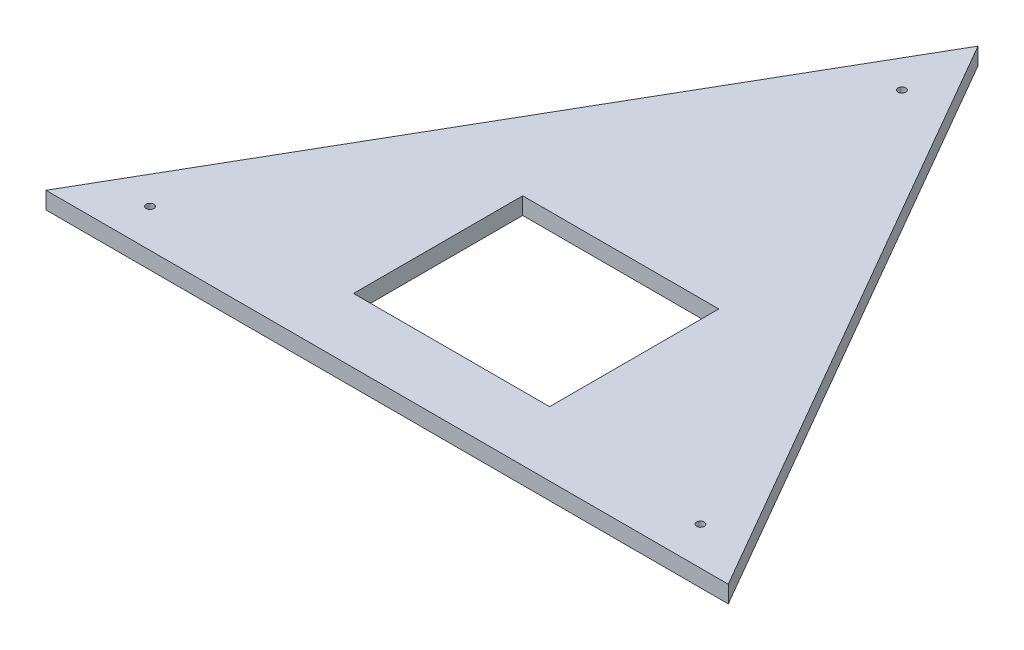
SolidWorks part; units mm, degrees
ref_plane "Front Plane" through (0, 0, 0) normal (0, 0, 1) x (1, 0, 0)
ref_plane "Top Plane" through (0, 0, 0) normal (0, 1, 0) x (1, 0, 0)
ref_plane "Right Plane" through (0, 0, 0) normal (1, 0, 0) x (0, 0, -1)
sketch "Sketch1" plane through (0, 0, 0) normal (0, 1, 0) x (1, 0, 0)
  line L1 (0, 146.647) -> (-127, -73.3235)
  line L2 (-127, -73.3235) -> (127, -73.3235)
  line L3 (127, -73.3235) -> (0, 146.647)
  circle A0 centre (0, 0) radius 73.3235 construction
  dimension "D1" = 254
extrude "Boss-Extrude1" add sketch "Sketch1" along normal blind 6.35
sketch "Sketch2" plane through (0, 6.35, 0) normal (0, 1, 0) x (1, 0, 0)
  line L0 (0, -59.3535) -> (0, -73.3235)
  line L1 (-82.55, -73.3235) -> (82.55, -73.3235)
  line L2 (-82.55, -73.3235) -> (-82.55, -59.3535)
  line L3 (-82.55, -59.3535) -> (82.55, -59.3535)
  line L4 (82.55, -73.3235) -> (82.55, -59.3535)
  line L5 (-127, -73.3235) -> (127, -73.3235) construction
  line L6 (0, -49.3535) -> (0, 13.6465)
  line L7 (-36.5, 13.6465) -> (36.5, 13.6465)
  line L8 (-36.5, 13.6465) -> (-36.5, -49.3535)
  line L9 (-36.5, -49.3535) -> (36.5, -49.3535)
  line L10 (36.5, 13.6465) -> (36.5, -49.3535)
  line L11 (-63.5, 36.6617) -> (-51.4016, 29.6767)
  line L12 (-104.775, -34.8287) -> (-22.225, 108.1521)
  line L13 (-104.775, -34.8287) -> (-92.6766, -41.8137)
  line L14 (-92.6766, -41.8137) -> (-10.1266, 101.1671)
  line L15 (-22.225, 108.1521) -> (-10.1266, 101.1671)
  line L16 (63.5, 36.6617) -> (51.4016, 29.6767)
  line L17 (22.225, 108.1521) -> (104.775, -34.8287)
  line L18 (22.225, 108.1521) -> (10.1266, 101.1671)
  line L19 (10.1266, 101.1671) -> (92.6766, -41.8137)
  line L20 (104.775, -34.8287) -> (92.6766, -41.8137)
  line L23 (0, 146.647) -> (-127, -73.3235) construction
  line L24 (127, -73.3235) -> (0, 146.647) construction
  line L25 (-104.775, -34.8287) -> (-82.55, -73.3235)
  line L26 (104.775, -34.8287) -> (82.55, -73.3235)
  line L27 (-22.225, 108.1521) -> (22.225, 108.1521)
  circle A0 centre (-102.4613, -59.1561) radius 1.4224
  circle A1 centre (102.4613, -59.1561) radius 1.4224
  circle A2 centre (0, 118.3121) radius 1.4224
  dimension "D11" = 2.8448
  dimension "D13" = 2.8448
  dimension "D15" = 2.8448
  dimension "D1" = 165.1
  dimension "D2" = 13.97
  dimension "D3" = 63
  dimension "D4" = 73
  dimension "D5" = 10
  dimension "D6" = 165.1
  dimension "D7" = 13.97
  dimension "D8" = 165.1
  dimension "D9" = 13.97
  dimension "D10" = 10.16
  dimension "D12" = 10.16
  dimension "D14" = 10.16
extrude "Cut-Extrude2" cut sketch "Sketch2" against normal through all contours L8 L9 L6 L7 | L10 L7 L6 L9 | A2 | A0 | A1
